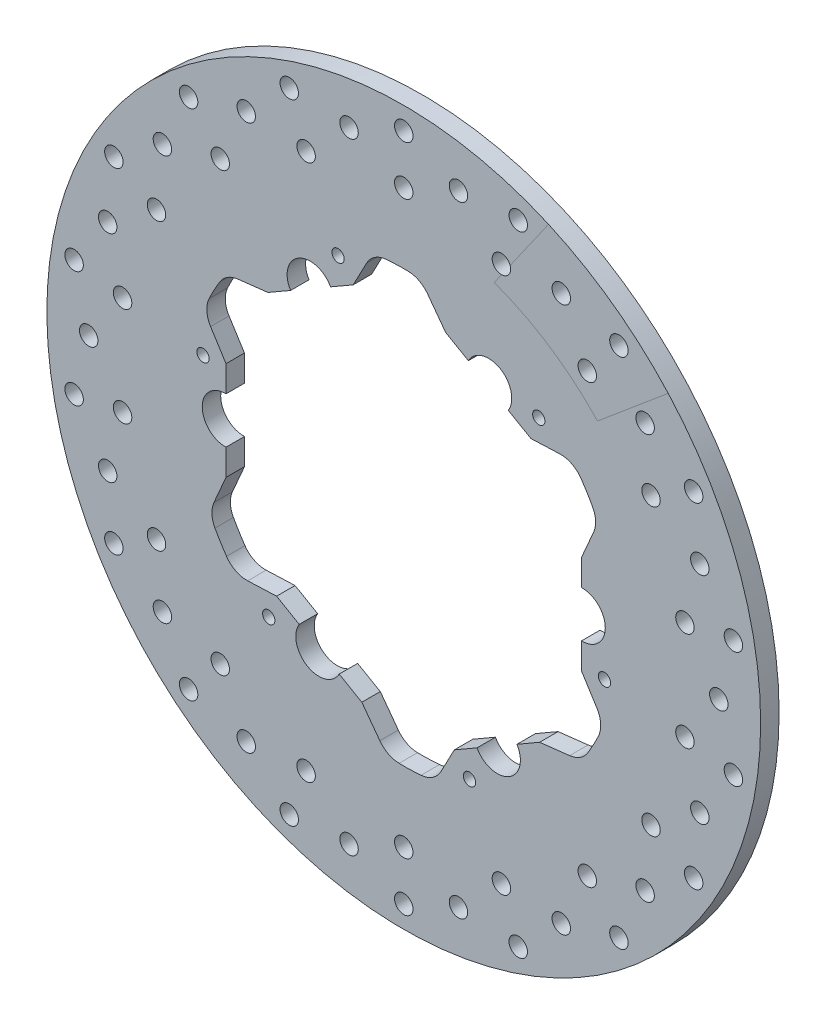
SolidWorks part; units mm, degrees
material "Gray Cast Iron"
ref_plane "Front Plane" through (0, 0, 0) normal (0, 0, 1) x (1, 0, 0)
ref_plane "Top Plane" through (0, 0, 0) normal (0, 1, 0) x (1, 0, 0)
ref_plane "Right Plane" through (0, 0, 0) normal (1, 0, 0) x (0, 0, -1)
sketch "Sketch1" plane through (0, 0, 0) normal (0, 0, 1) x (1, 0, 0)
  line L0 (-55.5625, 0) -> (-55.5625, -25.0191) construction
  line L1 (-45.8597, 11.4094) -> (-45.8597, 4.6599)
  line L2 (-45.8597, 11.4094) -> (-51.6236, 20.5474)
  line L3 (-45.8597, -13.9906) -> (-50.1583, -23.9026)
  line L4 (-45.8597, -7.2411) -> (-45.8597, -13.9906)
  line L5 (-13.049, 45.4204) -> (-8.0172, 54.981)
  line L6 (-13.049, 45.4204) -> (-18.8943, 42.0456)
  line L7 (-29.2008, 36.0951) -> (-35.0461, 32.7204)
  line L8 (-35.0461, 32.7204) -> (-45.7794, 31.4871)
  line L9 (32.8107, 34.011) -> (43.6064, 34.4336)
  line L10 (32.8107, 34.011) -> (26.9654, 37.3857)
  line L11 (16.6589, 43.3362) -> (10.8136, 46.711)
  line L12 (10.8136, 46.711) -> (4.3789, 55.3897)
  line L13 (45.8597, -11.4094) -> (51.6236, -20.5474)
  line L14 (45.8597, -11.4094) -> (45.8597, -4.6599)
  line L15 (45.8597, 7.2411) -> (45.8597, 13.9906)
  line L16 (45.8597, 13.9906) -> (50.1583, 23.9026)
  line L17 (13.049, -45.4204) -> (8.0172, -54.981)
  line L18 (13.049, -45.4204) -> (18.8943, -42.0456)
  line L19 (29.2008, -36.0951) -> (35.0461, -32.7204)
  line L20 (35.0461, -32.7204) -> (45.7794, -31.4871)
  line L21 (-32.8107, -34.011) -> (-43.6064, -34.4336)
  line L22 (-32.8107, -34.011) -> (-26.9654, -37.3857)
  line L23 (-16.6589, -43.3362) -> (-10.8136, -46.711)
  line L24 (-10.8136, -46.711) -> (-4.3789, -55.3897)
  circle A0 centre (0, 0) radius 92.075
  arc A1 (-45.7794, 31.4871) -> (-51.6236, 20.5474) centre (0, 0) ccw
  arc A3 (-45.8597, 4.6599) -> (-45.8597, -7.2411) centre (-46.0375, -1.2906) ccw
  arc A4 (-18.8943, 42.0456) -> (-29.2008, 36.0951) centre (-24.1364, 39.2243) ccw
  arc A5 (26.9654, 37.3857) -> (16.6589, 43.3362) centre (21.9011, 40.5149) ccw
  arc A6 (45.8597, -4.6599) -> (45.8597, 7.2411) centre (46.0375, 1.2906) ccw
  arc A7 (18.8943, -42.0456) -> (29.2008, -36.0951) centre (24.1364, -39.2243) ccw
  arc A8 (-26.9654, -37.3857) -> (-16.6589, -43.3362) centre (-21.9011, -40.5149) ccw
  arc A9 (4.3789, 55.3897) -> (-8.0172, 54.981) centre (0, 0) ccw
  arc A10 (50.1583, 23.9026) -> (43.6064, 34.4336) centre (0, 0) ccw
  arc A11 (45.7794, -31.4871) -> (51.6236, -20.5474) centre (0, 0) ccw
  arc A12 (-4.3789, -55.3897) -> (8.0172, -54.981) centre (0, 0) ccw
  arc A13 (-55.5625, 0) -> (-43.6064, -34.4336) centre (0, 0) ccw
  point P50 (0, 0)
  dimension "D1" = 184.15
  dimension "D2" = 111.125
  dimension "D3" = 11.9062
  dimension "D4" = 9.525
  dimension "D5" = 0.1778
  dimension "D6" = 25.4
  dimension "D7" = 44.45
  dimension "D9" = 47.2577
  dimension "D8" = 6
extrude "Boss-Extrude1" add sketch "Sketch1" along normal blind 4.7625
fillet "Fillet1" radius 6.35 12 edges at (8.0172, -54.981, 2.3813) (45.7794, -31.4871, 2.3813) (-4.3789, -55.3897, 2.3813) (-43.6064, -34.4336, 2.3813) (51.6236, -20.5474, 2.3813) (50.1583, 23.9026, 2.3813) (43.6064, 34.4336, 2.3813) (4.3789, 55.3897, 2.3813) (-50.1583, -23.9026, 2.3813) (-51.6236, 20.5474, 2.3813) (-8.0172, 54.981, 2.3813) (-45.7794, 31.4871, 2.3813)
sketch "Sketch4" plane through (0, 0, 4.7625) normal (0, 0, 1) x (1, 0, 0)
  circle A0 centre (-16.953, 50.0113) radius 1.5875
  arc A1 (-18.8943, 42.0456) -> (-29.2008, 36.0951) centre (-24.1364, 39.2243) ccw construction
  circle A3 centre (34.8346, 39.6874) radius 1.5875
  circle A4 centre (51.7876, -10.3239) radius 1.5875
  circle A5 centre (16.953, -50.0113) radius 1.5875
  circle A6 centre (-34.8346, -39.6874) radius 1.5875
  circle A7 centre (-51.7876, 10.3239) radius 1.5875
  point P6 (-27.113, 44.3799)
  point P23 (0, 0)
  dimension "D1" = 52.8066
  dimension "D2" = 3.175
  dimension "D3" = 10.16
  dimension "D4" = 6
extrude "Cut-Extrude1" cut sketch "Sketch4" against normal through all
sketch "Sketch5" plane through (0, 0, 4.7625) normal (0, 0, 1) x (1, 0, 0)
  line L0 (0, 120.6115) -> (0, 84.6416) construction
  line L1 (-74.0774, 0) -> (83.9652, 0) construction
  line L2 (0, 0) -> (20.7529, 117.6956) construction
  circle A0 centre (0, 0) radius 68.58 construction
  circle A4 centre (0, 86.36) radius 2.3812
  circle A5 centre (0, 73.66) radius 2.3812
  circle A6 centre (14.1141, 80.0452) radius 2.3812
  dimension "D1" = 137.16
  dimension "D2" = 4.7625
  dimension "D3" = 12.7
  dimension "D4" = 86.36
  dimension "D5" = 10
  dimension "D6" = 81.28
extrude "Cut-Extrude2" cut sketch "Sketch5" against normal through all
sketch "Sketch6" plane through (0, 0, 4.7625) normal (0, 0, 1) x (1, 0, 0)
  line L0 (0, 0) -> (0, 110.5188) construction
  line L1 (0, 0) -> (38.9978, 107.1456) construction
  line L4 (23.3472, 64.1458) -> (37.3582, 84.1556)
  line L5 (49.9701, 46.5054) -> (68.2294, 61.8268)
  arc A2 (68.2294, 61.8268) -> (37.3582, 84.1556) centre (0, 0) ccw
  arc A3 (49.9701, 46.5054) -> (23.3472, 64.1458) centre (0, 0) ccw
  dimension "D2" = 15
  dimension "D3" = 184.15
  dimension "D6" = 136.525
  dimension "D1" = 20
  dimension "D4" = 15
  dimension "D5" = 38.1
split line "Split Line1"
pattern_circular "FrontPaternCopy" count 18 over 360 about axis through (0, 0, 0) along (0, 0, 1) of "Cut-Extrude2"
sketch "Sketch7" plane through (0, 0, 4.7625) normal (0, 0, 1) x (1, 0, 0)
  line L0 (0, 0) -> (-24.1364, 39.2243) construction
move or copy body "Body-Move/Copy1" [suppressed] parameters "D1"=0, "D2"=0, "D3"=0
equation "\"holenumber\"=18"
equation "\"D1@FrontPaternCopy\"=\"holenumber\""
